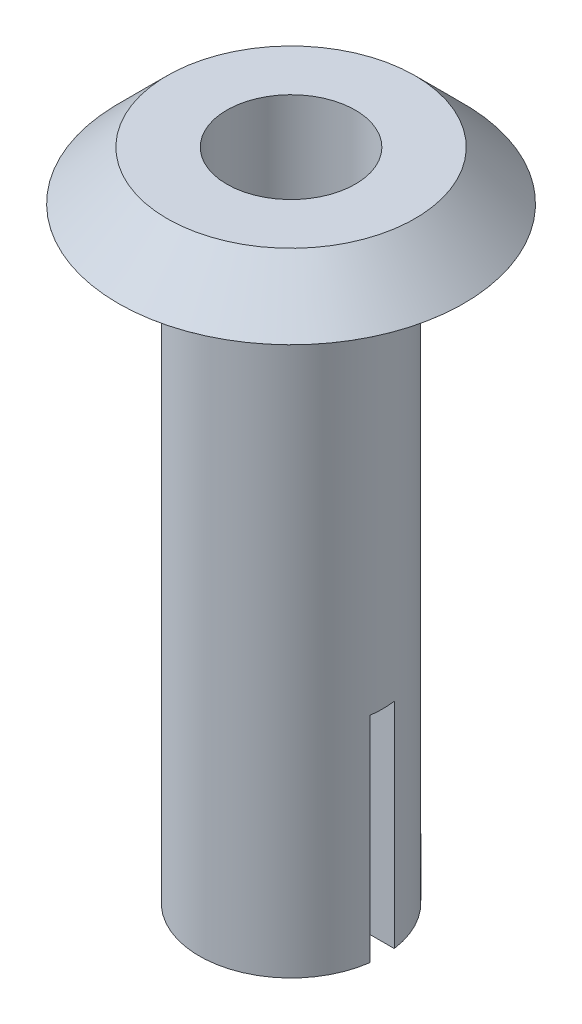
SolidWorks part; units mm, degrees
ref_plane "Alzado" through (0, 0, 0) normal (0, 0, 1) x (1, 0, 0)
ref_plane "Planta" through (0, 0, 0) normal (0, 1, 0) x (1, 0, 0)
ref_plane "Vista lateral" through (0, 0, 0) normal (1, 0, 0) x (0, 0, -1)
sketch "Croquis1" plane through (0, 0, 0) normal (0, 1, 0) x (1, 0, 0)
  circle A0 centre (0, 0) radius 1.5
extrude "Saliente-Extruir1" add sketch "Croquis1" along normal blind 10.7
sketch "Croquis2" plane through (0, 10.7, 0) normal (0, 1, 0) x (1, 0, 0)
  circle A0 centre (0, 0) radius 2.825
extrude "Saliente-Extruir2" add sketch "Croquis2" along normal blind 0.0001 and the other way blind 0.8
chamfer "Chaflán1" distance 0.8 angle 45 1 edges at (0, 10.7001, 2.825)
sketch "Croquis3" plane through (0, 10.7001, 0) normal (0, 1, 0) x (1, 0, 0)
  circle A0 centre (0, 0) radius 1.05
extrude "Cortar-Extruir1" cut sketch "Croquis3" against normal blind 10.4
fillet "Redondeo2" radius 0.8 1 edges at (0, 0.3001, 1.05)
sketch "Croquis6" plane through (0, 0, 0) normal (0, -1, 0) x (-1, 0, 0)
  line L1 (1.5, -0.2) -> (-1.5, -0.2)
  line L2 (1.5, -0.2) -> (1.5, 0.2)
  line L3 (1.5, 0.2) -> (-1.5, 0.2)
  line L4 (-1.5, -0.2) -> (-1.5, 0.2)
  line L5 (1.5, -0.2) -> (-1.5, 0.2) construction
  line L6 (1.5, 0.2) -> (-1.5, -0.2) construction
  point P0 (0, 0)
extrude "Cortar-Extruir4" cut sketch "Croquis6" against normal blind 3.5
